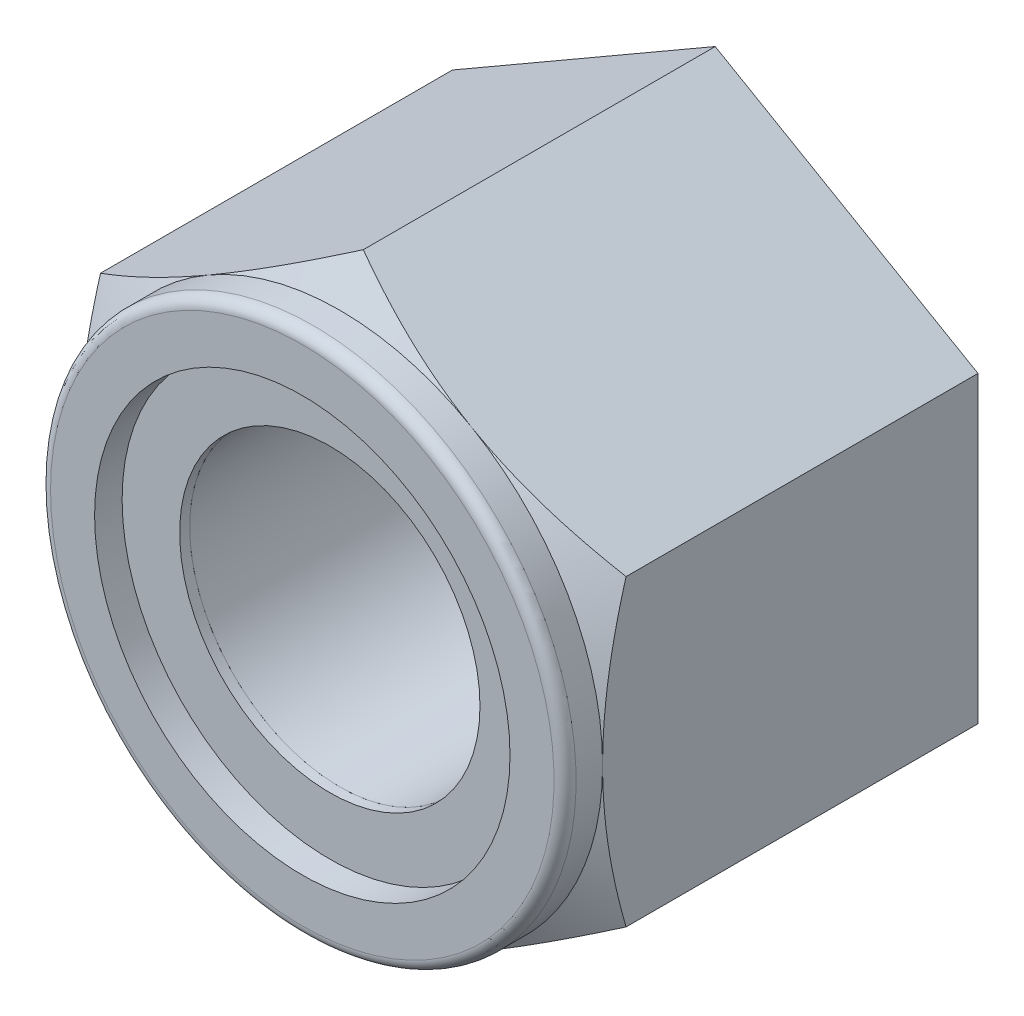
SolidWorks part; units mm, degrees
ref_plane "Front" through (0, 0, 0) normal (0, 0, 1) x (1, 0, 0)
ref_plane "Top" through (0, 0, 0) normal (0, 1, 0) x (1, 0, 0)
ref_plane "Right" through (0, 0, 0) normal (1, 0, 0) x (0, 0, -1)
sketch "Sketch1" plane through (0, 0, 0) normal (0, 0, 1) x (1, 0, 0)
  line L1 (0, 4.0415) -> (-3.5, 2.0207)
  line L2 (-3.5, 2.0207) -> (-3.5, -2.0207)
  line L3 (-3.5, -2.0207) -> (0, -4.0415)
  line L4 (0, -4.0415) -> (3.5, -2.0207)
  line L5 (3.5, -2.0207) -> (3.5, 2.0207)
  line L6 (3.5, 2.0207) -> (0, 4.0415)
  circle A0 centre (0, 0) radius 3.5 construction
  dimension "S" = 7
extrude "Extrude1" add sketch "Sketch1" along normal blind 5
sketch "Sketch2" plane through (0, 0, 0) normal (0, 1, 0) x (1, 0, 0)
  line L0 (3.5, -5) -> (4.9, -5)
  line L1 (4.9, -5) -> (4.9, -4.1917)
  line L2 (4.9, -4.1917) -> (3.5, -5)
  line L3 (0, 0) -> (0, -5) construction
  dimension "D1" = 30
  dimension "D2" = 1.4
revolve "Cut-Revolve1" cut sketch "Sketch2" angle 360 about L3
sketch "Sketch3" plane through (0, 0, 0) normal (0, 1, 0) x (1, 0, 0)
  line L0 (3.5, -5) -> (3.5, -5.5)
  line L1 (3.5, -5.5) -> (2.7667, -5.5)
  line L2 (2.7667, -5.5) -> (2.7667, -5.1333)
  line L3 (2.7667, -5.1333) -> (3.1333, -5.1333)
  line L4 (3.1333, -5) -> (3.1333, -5.1333)
  line L5 (1.75, -5) -> (3.5, -5) construction
  line L6 (3.5, 0) -> (0, 0) construction
  line L7 (3.5, -5) -> (3.1333, -5)
  line L8 (0, 0) -> (0, -5) construction
  line L9 (-1.75, -5) -> (1.75, -5) construction
  dimension "m" = 5.5
  dimension "D1" = 0.3667
  dimension "D2" = 0.7333
revolve "Revolve1" add sketch "Sketch3" angle 360 about L8
sketch "Sketch4" plane through (0, 0, 0) normal (0, 0, -1) x (-1, 0, 0)
  circle A0 centre (0, 0) radius 2
  dimension "d" = 4
sketch "Sketch5" plane through (0, 0, 5) normal (0, 0, 1) x (1, 0, 0)
  circle A0 centre (0, 0) radius 3.1333
  circle A1 centre (0, 0) radius 2
  circle A2 centre (0, 0) radius 3.1333 construction
  dimension "D1" = 4
extrude "Extrude2" add sketch "Sketch5" along normal up to surface (0.1333 mm away) separate body up to face at (-2.7667, 0, 5.1333)
extrude "Cut-Extrude1" cut sketch "Sketch4" against normal through all
fillet "Fillet2" radius 0.1467 1 edges at (-3.5, 0, 5.5)
equation "\"D2@Sketch2\" = \"S@Sketch1\" / 5"
equation "\"D1@Sketch3\" = \"m@Sketch3\" / 15"
equation "\"D2@Sketch3\" = \"D1@Sketch3\" * 2"
equation "\"D1@Sketch5\" = \"d@Sketch4\""
equation "\"D1@Fillet2\" = \"D2@Sketch3\" / 5"
